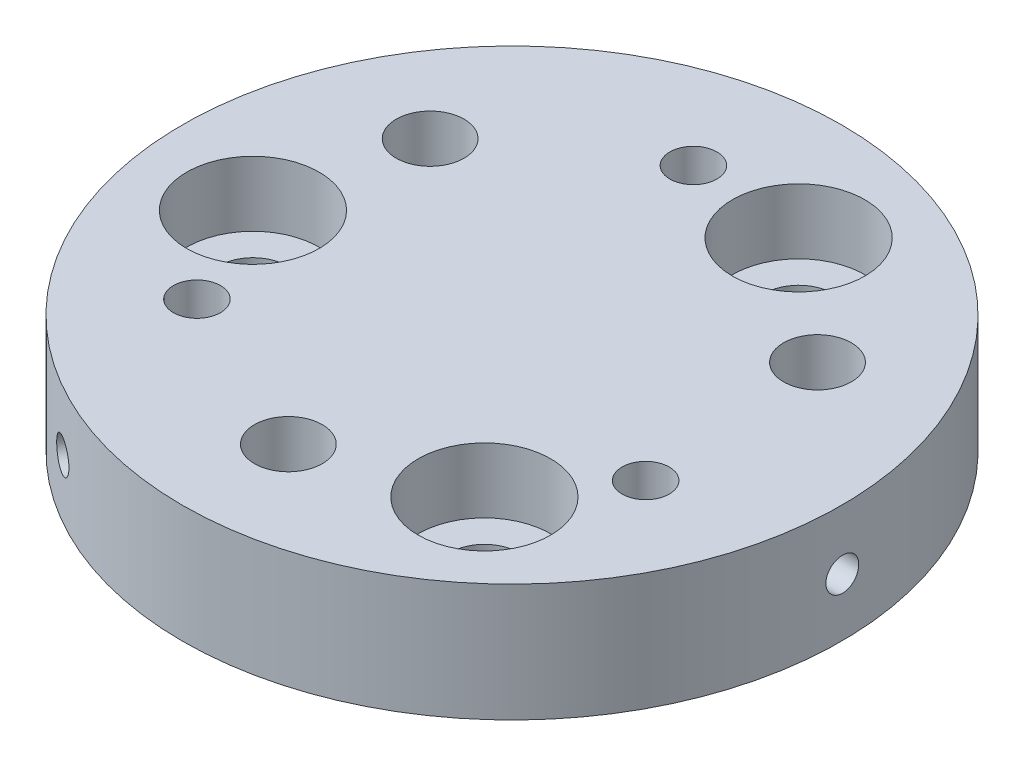
SolidWorks part; units mm, degrees
ref_plane "Front Plane" through (0, 0, 0) normal (0, 0, 1) x (1, 0, 0)
ref_plane "Top Plane" through (0, 0, 0) normal (0, 1, 0) x (1, 0, 0)
ref_plane "Right Plane" through (0, 0, 0) normal (1, 0, 0) x (0, 0, -1)
sketch "Sketch1" plane through (0, 0, 0) normal (0, 1, 0) x (1, 0, 0)
  circle A0 centre (0, 0) radius 17.78
  dimension "D1" = 35.56
extrude "Boss-Extrude1" add sketch "Sketch1" along normal blind 6.35
hole_wizard "CBORE for #6 Socket Head Cap Screw1" positions "Sketch3" profile "Sketch4" counterbore size "#6" standard "ANSI Inch" end condition through all
sketch "Sketch3" plane through (0, 6.35, 0) normal (0, 1, 0) x (1, 0, 0)
  line L3 (0, 0) -> (7.7552, -9.2423)
  point P0 (7.7552, -9.2423)
sketch "Sketch4" plane through (7.7552, 6.35, 9.2423) normal (1, 0, 0) x (0, 0, 1)
  line L0 (0, 0) -> (0, 6.35)
  line L1 (0, 6.35) -> (1.8288, 6.35)
  line L3 (1.8288, 6.35) -> (1.8288, 3.5052)
  line L4 (1.8288, 3.5052) -> (3.5725, 3.5052)
  line L5 (3.5725, 3.5052) -> (3.5725, 0)
  line L7 (3.5725, 0) -> (0, 0)
  line L11 (0, -6.35) -> (0, 107.95) construction
  dimension "Thru Hole Dia." = 3.6576
  dimension "Thru Hole Depth" = 6.35
  dimension "C'Bore Dia." = 7.145
  dimension "C'Bore Depth" = 3.5052
pattern_circular "CirPattern1" count 3 over 360 about axis through (0, 0, 0) along (0, 1, 0) of "CBORE for #6 Socket Head Cap Screw1"
sketch "Sketch9" plane through (0, 6.35, 0) normal (0, 1, 0) x (1, 0, 0)
  line L0 (0, 0) -> (10.4486, 6.0325)
  circle A0 centre (10.4486, 6.0325) radius 1.4122
ref_plane "Plane1" [suppressed] through (0, 3.175, 0) normal (0, 1, 0) x (1, 0, 0)
sketch "Sketch11" [suppressed] plane through (0, 3.175, 0) normal (0, 1, 0) x (1, 0, 0)
  line L0 (0, 0) -> (-7.135, -12.0105)
  circle A0 centre (0, 0) radius 13.97 construction
ref_plane "Plane2" [suppressed] through (-7.135, 3.175, 12.0105) normal (-0.5107, 0, 0.8597) x (0.8597, 0, 0.5107)
hole_wizard "Tap Drill for #2-56 Tap1" positions "3DSketch3" profile "Sketch15" hole size "#2-56" standard "ANSI Inch"
sketch3d "3DSketch3"
  point P0 (-8.8359, 3.1056, 15.429)
sketch "Sketch15" plane through (-8.8359, 3.1056, 15.429) normal (0, 1, 0) x (0.8678, 0, 0.497)
  line L0 (0, 0) -> (0, 7.096)
  line L1 (0, 7.096) -> (0.889, 6.35)
  line L2 (0.889, 6.35) -> (0.889, 0)
  line L5 (0.889, 0) -> (0, 0)
  line L10 (0, 7.096) -> (-0.889, 6.35) construction
  line L11 (0, -6.35) -> (0, 107.95) construction
  dimension "Hole Dia." = 1.778
  dimension "Hole Depth" = 6.35
  dimension "Drill Angle" = 100
pattern_circular "CirPattern3" count 3 every 120 about axis through (0, 6.35, 0) along (0, -1, 0) of "Tap Drill for #2-56 Tap1"
sketch "Sketch17" plane through (0, 0, 0) normal (0, -1, 0) x (1, 0, 0)
  line L0 (0, 0) -> (10.4486, -6.0325)
hole_wizard "CBORE for #6 Socket Head Cap Screw2" positions "3DSketch4" profile "Sketch18" counterbore size "#6" standard "ANSI Inch" end condition through all
sketch3d "3DSketch4"
  point P0 (10.4486, 0, -6.0325)
sketch "Sketch18" plane through (10.4486, 0, -6.0325) normal (1, 0, 0) x (0, 0, -1)
  line L0 (0, 0) -> (0, 6.35)
  line L1 (0, 6.35) -> (1.8288, 6.35)
  line L3 (1.8288, 6.35) -> (1.8288, 3.5052)
  line L4 (1.8288, 3.5052) -> (3.5725, 3.5052)
  line L5 (3.5725, 3.5052) -> (3.5725, 0)
  line L7 (3.5725, 0) -> (0, 0)
  line L11 (0, -6.35) -> (0, 107.95) construction
  dimension "Thru Hole Dia." = 3.6576
  dimension "Thru Hole Depth" = 6.35
  dimension "C'Bore Dia." = 7.145
  dimension "C'Bore Depth" = 3.5052
pattern_circular "CirPattern4" count 3 every 120 about axis through (0, 0, 0) along (0, 1, 0) of "CBORE for #6 Socket Head Cap Screw2"
sketch "Sketch19" plane through (0, 6.35, 0) normal (0, 1, 0) x (1, 0, 0)
  line L0 (0, 0) -> (11.3374, -4.1265)
  circle A0 centre (11.3374, -4.1265) radius 1.27
extrude "Cut-Extrude1" cut sketch "Sketch19" against normal through all contours A0
pattern_circular "CirPattern5" count 3 every 120 about axis through (0, 0, 0) along (0, 1, 0) of "Cut-Extrude1"
